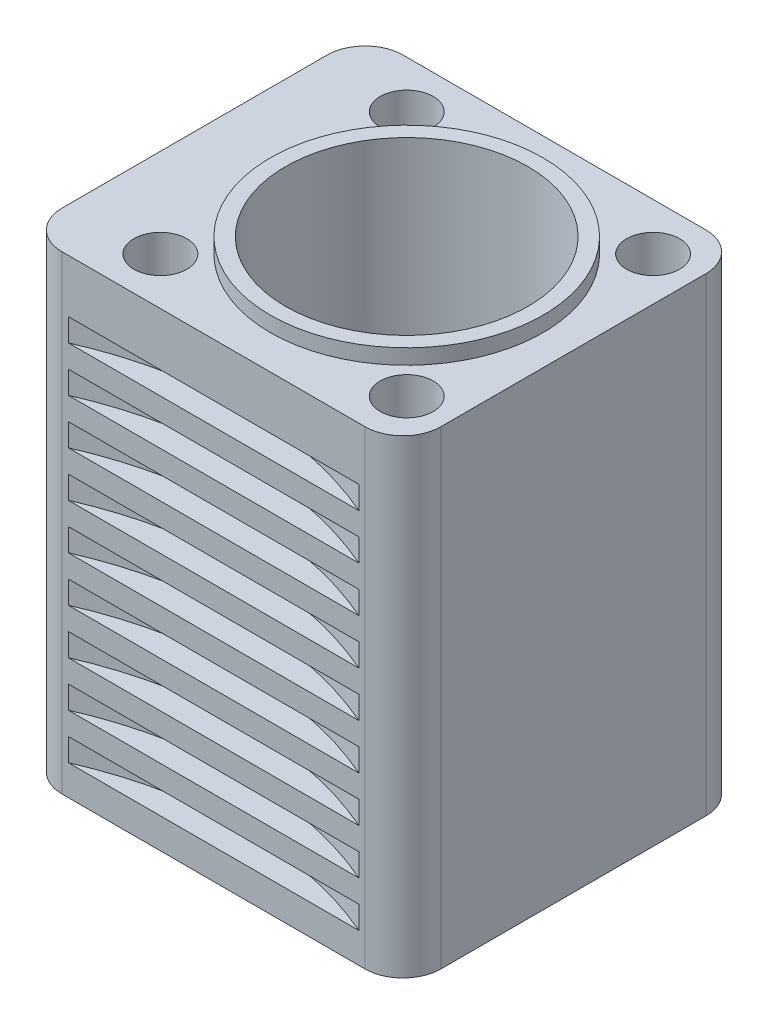
SolidWorks part; units mm, degrees
ref_plane "Front Plane" through (0, 0, 0) normal (0, 0, 1) x (1, 0, 0)
ref_plane "Top Plane" through (0, 0, 0) normal (0, 1, 0) x (1, 0, 0)
ref_plane "Right Plane" through (0, 0, 0) normal (1, 0, 0) x (0, 0, -1)
sketch "Sketch1" plane through (0, 0, 0) normal (0, 1, 0) x (1, 0, 0)
  line L1 (-23, 22.5) -> (17, 22.5)
  line L2 (-28, 17.5) -> (-28, -17.5)
  line L3 (-23, -22.5) -> (17, -22.5)
  line L4 (22, 17.5) -> (22, -17.5)
  arc A0 (17, 22.5) -> (22, 17.5) centre (17, 17.5) cw
  arc A1 (17, -22.5) -> (22, -17.5) centre (17, -17.5) ccw
  arc A2 (-28, -17.5) -> (-23, -22.5) centre (-23, -17.5) ccw
  arc A3 (-23, 22.5) -> (-28, 17.5) centre (-23, 17.5) ccw
  point P7 (22, 22.5)
  point P10 (22, -22.5)
  point P15 (-28, 22.5)
  dimension "D5" = 5
  dimension "D1" = 50
  dimension "D2" = 45
  dimension "D3" = 22
  dimension "D4" = 22.5
extrude "Boss-Extrude1" add sketch "Sketch1" along normal blind 62
sketch "Sketch2" plane through (0, 62, 0) normal (0, 1, 0) x (1, 0, 0)
  circle A0 centre (0, 0) radius 18
  dimension "D1" = 36
extrude "Boss-Extrude2" add sketch "Sketch2" along normal blind 2
sketch "Sketch3" plane through (0, 64, 0) normal (0, 1, 0) x (1, 0, 0)
  circle A0 centre (0, 0) radius 16
  dimension "D1" = 32
extrude "Cut-Extrude1" cut sketch "Sketch3" against normal through all
sketch "Sketch4" plane through (0, 0, 0) normal (0, -1, 0) x (1, 0, 0)
  line L0 (-28, -17.5) -> (-28, 17.5) construction
  line L1 (-22.61, 2) -> (-8.7, 2)
  line L3 (-22.61, -2) -> (-8.7, -2)
  line L4 (-8.7, 2) -> (-8.7, -2)
  arc A0 (-22.61, 2) -> (-22.61, -2) centre (-22.61, 0) ccw
  dimension "D1" = 4
  dimension "D2" = 2
  dimension "D3" = 5.39
extrude "Cut-Extrude2" cut sketch "Sketch4" against normal blind 2
sketch "Sketch5" plane through (0, 0, 0) normal (0, -1, 0) x (1, 0, 0)
  line L0 (0, 0) -> (23, 0) construction
  line L1 (0, 0) -> (16.2635, 16.2635) construction
  circle A0 centre (0, 0) radius 23 construction
  circle A1 centre (16.2635, 16.2635) radius 3.5
  circle A2 centre (16.2635, -16.2635) radius 3.5
  circle A3 centre (-16.2635, -16.2635) radius 3.5
  circle A4 centre (-16.2635, 16.2635) radius 3.5
  point P15 (0, 0)
  dimension "D1" = 46
  dimension "D3" = 7
  dimension "D2" = 45
  dimension "D4" = 4
extrude "Cut-Extrude3" cut sketch "Sketch5" against normal through all
ref_plane "Plane1" through (-3, 0, 0) normal (1, 0, 0) x (0, 0, -1)
sketch "Sketch6" plane through (-3, 0, 0) normal (1, 0, 0) x (0, 0, -1)
  line L0 (-17.5, 0) -> (17.5, 0) construction
  line L1 (-18.5, 7) -> (-66.5, 7)
  line L2 (-18.5, 7) -> (-18.5, 4)
  line L3 (-18.5, 4) -> (-66.5, 4)
  line L4 (-66.5, 7) -> (-66.5, 4)
  line L6 (-22.5, 62) -> (-22.5, 0) construction
  dimension "D1" = 4
  dimension "D2" = 3
  dimension "D3" = 48
  dimension "D4" = 4
revolve "Cut-Revolve1" cut sketch "Sketch6" angle 360 about L4
pattern_linear "LPattern1" count 9 spacing 6 along (0, 1, 0) of "Cut-Revolve1"
mirror "Mirror1" about plane through (0, 0, 0) normal (0, 0, 1) of "LPattern1", "Cut-Revolve1"
sketch "Sketch8" plane through (0, 0, 0) normal (0, 0, 1) x (1, 0, 0)
  line L0 (-23, 0) -> (17, 0) construction
  line L1 (-24, 7) -> (-72, 7)
  line L2 (-24, 7) -> (-24, 4)
  line L3 (-24, 4) -> (-72, 4)
  line L4 (-72, 7) -> (-72, 4)
  line L5 (-28, 62) -> (-28, 0) construction
  dimension "D1" = 4
  dimension "D2" = 4
  dimension "D3" = 3
  dimension "D4" = 48
revolve "Cut-Revolve3" cut sketch "Sketch8" angle 360 about L4
pattern_linear "LPattern2" count 9 spacing 6 along (0, 1, 0) of "Cut-Revolve3"
